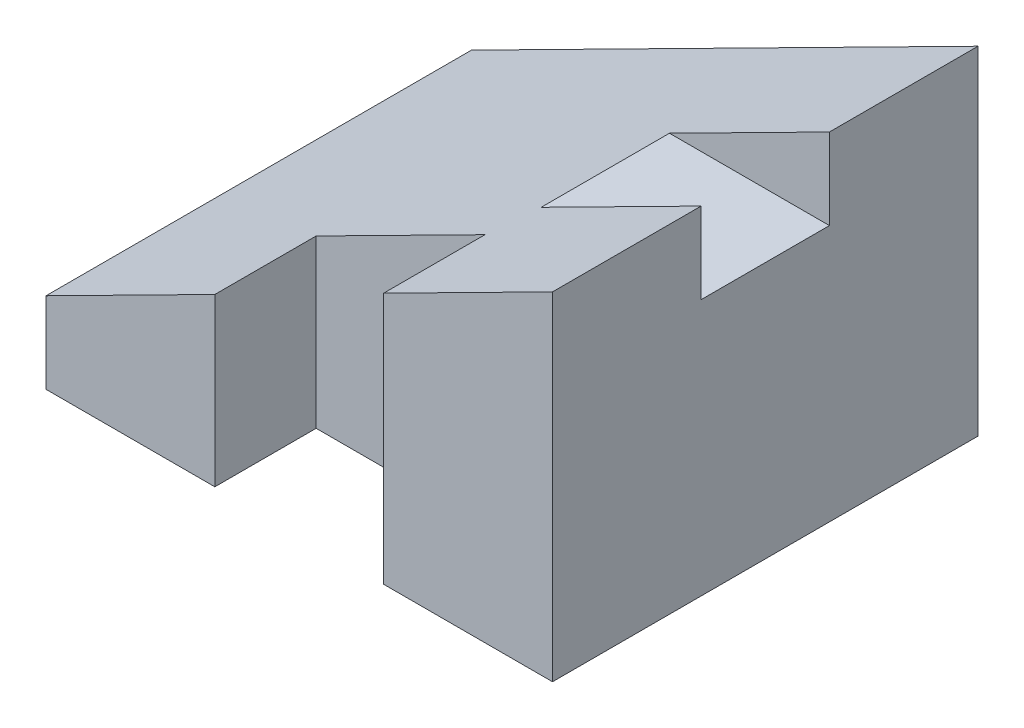
SolidWorks part; units mm, degrees
ref_plane "Front Plane" through (0, 0, 0) normal (0, 0, 1) x (1, 0, 0)
ref_plane "Top Plane" through (0, 0, 0) normal (0, 1, 0) x (1, 0, 0)
ref_plane "Right Plane" through (0, 0, 0) normal (1, 0, 0) x (0, 0, -1)
sketch "Sketch1" plane through (0, 0, 0) normal (0, 0, 1) x (1, 0, 0)
  line L0 (75, 0) -> (0, 0)
  line L1 (0, 0) -> (0, 12)
  line L2 (0, 12) -> (75, 50)
  line L3 (75, 50) -> (75, 0)
  dimension "D1" = 75
  dimension "D2" = 50
  dimension "D3" = 12
extrude "Boss-Extrude1" add sketch "Sketch1" along normal blind 63
sketch "Sketch2" plane through (0, 0, 63) normal (0, 0, 1) x (1, 0, 0)
  line L0 (25, 24.6667) -> (25, 0)
  line L1 (75, 50) -> (0, 12) construction
  line L2 (0, 0) -> (75, 0) construction
  line L3 (50, 37.3333) -> (50, 0)
  line L4 (50, 0) -> (25, 0)
  line L5 (25, 24.6667) -> (50, 37.3333)
  dimension "D1" = 25
  dimension "D2" = 25
extrude "Cut-Extrude1" cut sketch "Sketch2" against normal blind 15
sketch "Sketch6" plane through (75, 0, 0) normal (1, 0, 0) x (0, 0, -1)
  line L0 (-41, 50) -> (-41, 38)
  line L1 (-63, 50) -> (0, 50) construction
  line L2 (-41, 38) -> (-22, 38)
  line L3 (-22, 38) -> (-22, 50)
  line L4 (-41, 50) -> (-22, 50)
  line L5 (-63, 0) -> (-63, 50) construction
  line L6 (0, 0) -> (0, 50) construction
  point P8 (-41, 44)
  dimension "D1" = 12
  dimension "D2" = 22
  dimension "D3" = 22
extrude "Cut-Extrude3" cut sketch "Sketch6" against normal blind 25
